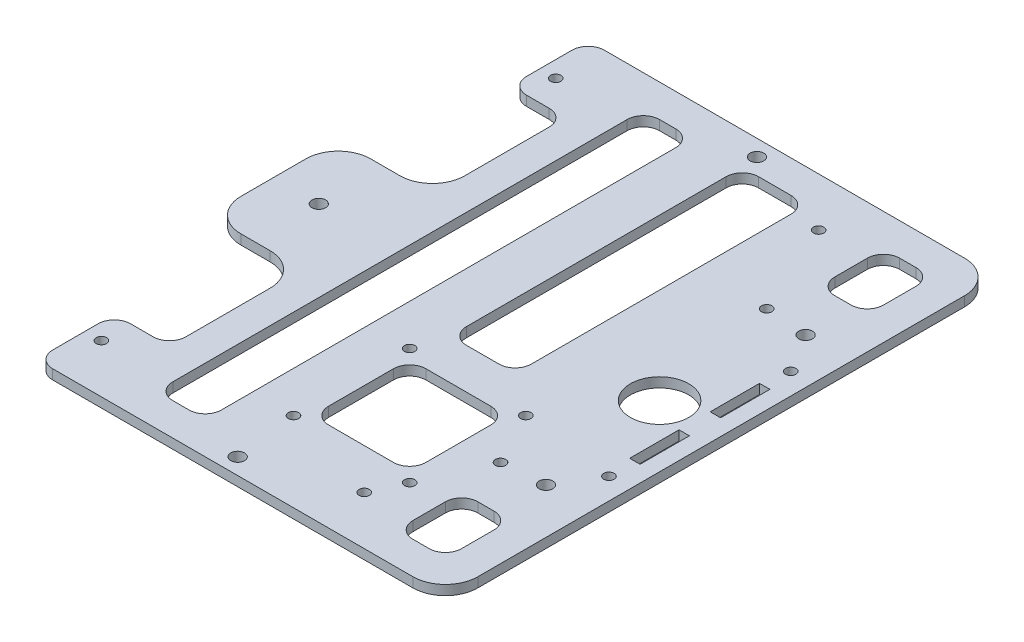
SolidWorks part; units mm, degrees
ref_plane "Front Plane" through (0, 0, 0) normal (0, 0, 1) x (1, 0, 0)
ref_plane "Top Plane" through (0, 0, 0) normal (0, 1, 0) x (1, 0, 0)
ref_plane "Right Plane" through (0, 0, 0) normal (1, 0, 0) x (0, 0, -1)
sketch "Sketch1" plane through (0, 0, 0) normal (0, 1, 0) x (1, 0, 0)
  line L1 (0, 0) -> (138, 0)
  line L2 (0, 0) -> (0, 170)
  line L3 (0, 170) -> (138, 170)
  line L4 (138, 0) -> (138, 170)
  dimension "D1" = 138
  dimension "D2" = 170
extrude "Boss-Extrude1" add sketch "Sketch1" along normal blind 3
sketch "Sketch2" plane through (0, 3, 0) normal (0, 1, 0) x (1, 0, 0)
  line L0 (0, 132) -> (138, 132) construction
  line L1 (0, 170) -> (29, 170)
  line L2 (0, 170) -> (0, 140)
  line L3 (0, 140) -> (29, 140)
  line L4 (29, 170) -> (29, 140)
  line L5 (138, 170) -> (109, 170)
  line L6 (138, 170) -> (138, 140)
  line L7 (138, 140) -> (109, 140)
  line L8 (109, 170) -> (109, 140)
  line L9 (138, 0) -> (109, 0)
  line L10 (138, 0) -> (138, 30)
  line L11 (138, 30) -> (109, 30)
  line L12 (109, 0) -> (109, 30)
  line L13 (0, 0) -> (29, 0)
  line L14 (0, 0) -> (0, 30)
  line L15 (0, 30) -> (29, 30)
  line L16 (29, 0) -> (29, 30)
  line L18 (0, 38) -> (138, 38) construction
  line L20 (29, 165) -> (109, 165) construction
  line L21 (29, 5) -> (109, 5) construction
  line L22 (69, 165) -> (69, 5) construction
  line L23 (138, 0) -> (138, 170) construction
  line L24 (69, 85) -> (138, 85) construction
  line L25 (0, 170) -> (0, 0) construction
  line L26 (10, 160) -> (10, 10)
  line L27 (10, 10) -> (128, 10)
  line L28 (128, 10) -> (128, 160)
  line L29 (128, 160) -> (10, 160)
  line L30 (10, 160) -> (10, 10) construction
  line L31 (10, 10) -> (128, 10) construction
  line L32 (128, 10) -> (128, 160) construction
  line L33 (128, 160) -> (10, 160) construction
  line L34 (138, 170) -> (0, 170) construction
  circle A220 centre (69, 165) radius 2.1
  circle A221 centre (69, 5) radius 2.1
  point P225 (69, 170)
  dimension "D12" = 4.2
  dimension "D13" = 4.2
  dimension "D1" = 30
  dimension "D2" = 160
  dimension "D5" = 8
  dimension "D9" = 30
  dimension "D10" = 80
  dimension "D11" = 8
  dimension "D3" = 10
extrude "Cut-Extrude1" cut sketch "Sketch2" against normal blind 3
sketch "Sketch3" plane through (0, 3, 0) normal (0, 1, 0) x (1, 0, 0)
  line L0 (69, 170) -> (69, 139.75) construction
  line L1 (14, 139.75) -> (124, 139.75) construction
  line L2 (14, 139.75) -> (14, 30.25) construction
  line L3 (14, 30.25) -> (124, 30.25) construction
  line L4 (124, 139.75) -> (124, 30.25) construction
  line L5 (109, 170) -> (29, 170) construction
  line L7 (14, 85) -> (0, 85) construction
  line L8 (0, 140) -> (0, 30) construction
  circle A0 centre (14, 125) radius 2.1
  circle A1 centre (14, 45) radius 2.1
  circle A2 centre (14, 85) radius 2.1
  circle A3 centre (124, 45) radius 2.1
  circle A5 centre (124, 125) radius 2.1
  dimension "D3" = 4.2
  dimension "D4" = 40
  dimension "D1" = 109.5
  dimension "D2" = 110
  dimension "D5" = 40
extrude "Cut-Extrude2" cut sketch "Sketch3" against normal through all
sketch "Sketch4" plane through (0, 0, 0) normal (0, 1, 0) x (1, 0, 0)
  line L0 (109, 170) -> (29, 170) construction
  line L1 (-2, 181) -> (140, 181)
  line L2 (-2, 181) -> (-2, -11)
  line L3 (-2, -11) -> (140, -11)
  line L4 (140, 181) -> (140, -11)
  line L6 (138, 30) -> (138, 140) construction
  point P6 (69, 170)
  point P7 (69, 181)
  point P12 (138, 85)
  point P13 (-2, 85)
  dimension "D1" = 192
  dimension "D2" = 142
sketch "Sketch5" plane through (0, 3, 0) normal (0, 1, 0) x (1, 0, 0)
  line L0 (29, 140) -> (29, 170) construction
  line L1 (0, 140) -> (29, 140)
  line L2 (0, 140) -> (0, 105)
  line L3 (0, 105) -> (29, 105)
  line L4 (29, 140) -> (29, 105)
  line L5 (0, 30) -> (29, 30)
  line L6 (0, 30) -> (0, 65)
  line L7 (0, 65) -> (29, 65)
  line L8 (29, 30) -> (29, 65)
  dimension "D1" = 35
extrude "Cut-Extrude3" cut sketch "Sketch5" against normal through all
sketch "Sketch6" plane through (0, 3, 0) normal (0, 1, 0) x (1, 0, 0)
  line L0 (138, 30) -> (138, 140) construction
  line L1 (129.8, 105) -> (133, 105)
  line L2 (129.8, 105) -> (129.8, 89.8)
  line L3 (129.8, 89.8) -> (133, 89.8)
  line L4 (133, 105) -> (133, 89.8)
  line L5 (109, 140) -> (138, 140) construction
  line L6 (0, 85) -> (138, 85) construction
  line L7 (0, 105) -> (0, 65) construction
  line L8 (129.8, 80.2) -> (133, 80.2)
  line L9 (133, 65) -> (133, 80.2)
  line L10 (129.8, 65) -> (133, 65)
  line L11 (129.8, 65) -> (129.8, 80.2)
  line L12 (131.4, 113) -> (131.4, 57) construction
  circle A0 centre (131.4, 113) radius 1.6
  circle A1 centre (131.4, 57) radius 1.6
  point P21 (131.4, 105)
  dimension "D5" = 3.2
  dimension "D6" = 8
  dimension "D1" = 5
  dimension "D2" = 3.2
  dimension "D3" = 35
  dimension "D4" = 15.2
  dimension "D7" = 8
extrude "Cut-Extrude4" cut sketch "Sketch6" against normal through all
sketch "Sketch9" plane through (0, 3, 0) normal (0, 1, 0) x (1, 0, 0)
  line L1 (109, 170) -> (138, 170)
  line L2 (109, 170) -> (109, 140)
  line L3 (109, 140) -> (138, 140)
  line L4 (138, 170) -> (138, 140)
  line L5 (109, 0) -> (138, 0)
  line L6 (109, 0) -> (109, 30)
  line L7 (109, 30) -> (138, 30)
  line L8 (138, 0) -> (138, 30)
extrude "Boss-Extrude2" add sketch "Sketch9" against normal up to surface (3 mm away) up to face at (131.4, 0, -55.4)
sketch "Sketch11" plane through (0, 3, 0) normal (0, 1, 0) x (1, 0, 0)
  line L0 (107.8, 85) -> (-2, 85) construction
  line L1 (107.8, 103.5) -> (129.8, 103.5)
  line L2 (107.8, 103.5) -> (107.8, 66.5)
  line L3 (107.8, 66.5) -> (129.8, 66.5)
  line L4 (129.8, 103.5) -> (129.8, 66.5)
  line L5 (-2, 181) -> (-2, -11) construction
  line L6 (129.8, 105) -> (129.8, 89.8) construction
  dimension "D1" = 22
  dimension "D2" = 37
sketch "Sketch10" plane through (0, 3, 0) normal (0, 1, 0) x (1, 0, 0)
  line L1 (64, 63) -> (105, 63) construction
  line L2 (64, 63) -> (64, 22) construction
  line L3 (64, 22) -> (105, 22) construction
  line L4 (105, 63) -> (105, 22) construction
  line L5 (29, 0) -> (29, 65) construction
  line L6 (65, 62) -> (104, 62) construction
  line L7 (104, 62) -> (104, 23) construction
  line L8 (65, 23) -> (104, 23) construction
  line L9 (65, 62) -> (65, 23) construction
  line L10 (29, 0) -> (138, 0) construction
  line L11 (74.5, 57.5) -> (94.5, 57.5)
  line L12 (69.5, 52.5) -> (69.5, 32.5)
  line L13 (74.5, 27.5) -> (94.5, 27.5)
  line L14 (99.5, 52.5) -> (99.5, 32.5)
  circle A0 centre (66.6, 60.4) radius 1.6
  circle A1 centre (102.4, 60.4) radius 1.6
  circle A2 centre (66.6, 24.6) radius 1.6
  circle A3 centre (102.4, 24.6) radius 1.6
  arc A4 (69.5, 32.5) -> (74.5, 27.5) centre (74.5, 32.5) ccw
  arc A5 (94.5, 27.5) -> (99.5, 32.5) centre (94.5, 32.5) ccw
  arc A6 (94.5, 57.5) -> (99.5, 52.5) centre (94.5, 52.5) cw
  arc A7 (74.5, 57.5) -> (69.5, 52.5) centre (74.5, 52.5) ccw
  point P24 (104, 42.5)
  point P25 (99.5, 42.5)
  point P26 (84.5, 23)
  point P27 (84.5, 27.5)
  point P32 (99.5, 27.5)
  point P35 (99.5, 57.5)
  dimension "D4" = 3.2
  dimension "D7" = 5
  dimension "D1" = 41
  dimension "D2" = 35
  dimension "D5" = 22
  dimension "D6" = 30
  dimension "D3" = 1
extrude "Cut-Extrude5" cut sketch "Sketch10" against normal through all
fillet "Fillet1" radius 10 6 edges at (138, 1.5, 0) (29, 1.5, 0) (0, 1.5, -65) (0, 1.5, -105) (138, 1.5, -170) (29, 1.5, -170)
fillet "Fillet2" radius 10 2 edges at (29, 1.5, -105) (29, 1.5, -65)
sketch "Sketch12" plane through (0, 3, 0) normal (0, 1, 0) x (1, 0, 0)
  line L0 (107.8, 85) -> (-2, 85) construction
  line L1 (39, 160) -> (54, 160)
  line L2 (39, 160) -> (39, 10)
  line L3 (39, 10) -> (54, 10)
  line L4 (54, 160) -> (54, 10)
  line L5 (29, 115) -> (29, 160) construction
  line L6 (128, 170) -> (39, 170) construction
  point P6 (39, 85)
  dimension "D1" = 10
  dimension "D2" = 10
  dimension "D3" = 15
extrude "Cut-Extrude6" cut sketch "Sketch12" against normal through all
fillet "Fillet3" radius 5 4 edges at (54, 1.5, -10) (39, 1.5, -10) (54, 1.5, -160) (39, 1.5, -160)
sketch "Sketch13" plane through (0, 3, 0) normal (0, 1, 0) x (1, 0, 0)
  line L0 (107.8, 85) -> (-2, 85) construction
  line L5 (138, 10) -> (138, 160) construction
  line L6 (44, 10) -> (49, 10) construction
  line L7 (113, 160) -> (128, 160)
  line L8 (113, 160) -> (113, 140)
  line L9 (113, 140) -> (128, 140)
  line L10 (128, 160) -> (128, 140)
  line L11 (113, 30) -> (128, 30)
  line L12 (113, 30) -> (113, 10)
  line L13 (113, 10) -> (128, 10)
  line L14 (128, 30) -> (128, 10)
  line L15 (49, 160) -> (44, 160) construction
  circle A0 centre (119, 85) radius 9
  dimension "D1" = 19
  dimension "D2" = 18
  dimension "D3" = 10
  dimension "D4" = 20
  dimension "D5" = 15
extrude "Cut-Extrude7" cut sketch "Sketch13" against normal through all
fillet "Fillet4" radius 5 8 edges at (128, 1.5, -160) (113, 1.5, -160) (113, 1.5, -140) (128, 1.5, -140) (113, 1.5, -30) (128, 1.5, -30) (128, 1.5, -10) (113, 1.5, -10)
sketch "Sketch14" plane through (0, 3, 0) normal (0, 1, 0) x (1, 0, 0)
  line L0 (128, 170) -> (39, 170) construction
  line L1 (39, 170) -> (12, 170)
  line L2 (39, 170) -> (39, 146)
  line L3 (39, 146) -> (12, 146)
  line L4 (12, 170) -> (12, 146)
  line L5 (39, 0) -> (12, 0)
  line L6 (39, 0) -> (39, 24)
  line L7 (39, 24) -> (12, 24)
  line L8 (12, 0) -> (12, 24)
  line L9 (39, 0) -> (128, 0) construction
  arc A0 (39, 170) -> (29, 160) centre (39, 160) ccw construction
  arc A1 (29, 10) -> (39, 0) centre (39, 10) ccw construction
  circle A2 centre (17, 155) radius 1.6
  circle A3 centre (17, 15) radius 1.6
  dimension "D1" = 27
  dimension "D2" = 24
extrude "Boss-Extrude3" add sketch "Sketch14" against normal up to surface (3 mm away) up to face at (120.5, 0, -150)
sketch "Sketch15" plane through (0, 3, 0) normal (0, 1, 0) x (1, 0, 0)
  circle A0 centre (111, 44) radius 1.6
  circle A1 centre (111, 126) radius 1.6
  circle A2 centre (98, 155) radius 1.6
  circle A3 centre (98, 15) radius 1.6
extrude "Cut-Extrude8" cut sketch "Sketch15" against normal through all
fillet "Fillet5" radius 5 6 edges at (29, 1.5, -146) (29, 1.5, -24) (12, 1.5, -24) (12, 1.5, 0) (12, 1.5, -146) (12, 1.5, -170)
sketch "Sketch16" plane through (0, 3, 0) normal (0, 1, 0) x (1, 0, 0)
  line L0 (49, 160) -> (44, 160) construction
  line L1 (69.5, 160) -> (89.5, 160)
  line L2 (69.5, 160) -> (69.5, 70)
  line L3 (69.5, 70) -> (89.5, 70)
  line L4 (89.5, 160) -> (89.5, 70)
  line L6 (17, 0) -> (128, 0) construction
  line L7 (69.5, 52.5) -> (69.5, 32.5) construction
  dimension "D2" = 20
  dimension "D3" = 70
extrude "Cut-Extrude9" cut sketch "Sketch16" against normal through all
fillet "Fillet6" radius 5 4 edges at (69.5, 1.5, -70) (89.5, 1.5, -70) (89.5, 1.5, -160) (69.5, 1.5, -160)
